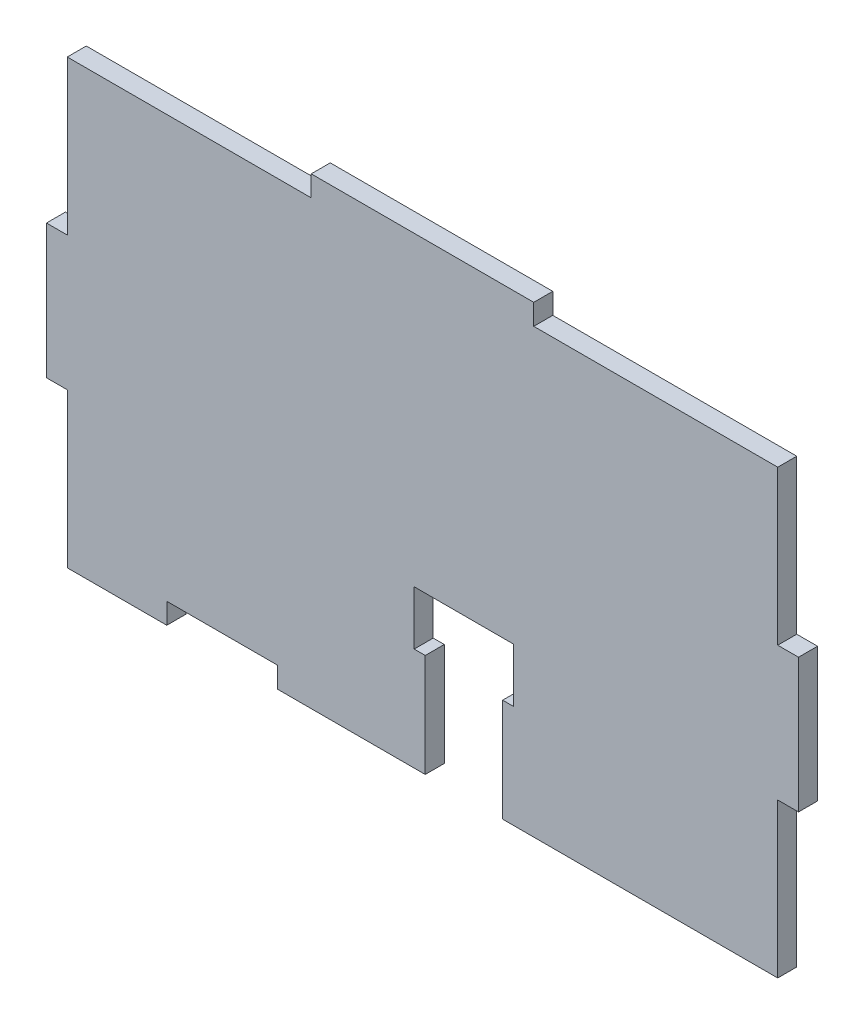
SolidWorks part; units mm, degrees
ref_plane "Front Plane" through (0, 0, 0) normal (0, 0, 1) x (1, 0, 0)
ref_plane "Top Plane" through (0, 0, 0) normal (0, 1, 0) x (1, 0, 0)
ref_plane "Right Plane" through (0, 0, 0) normal (1, 0, 0) x (0, 0, -1)
sketch "Sketch1" plane through (0, 0, 0) normal (0, 0, 1) x (1, 0, 0)
  line L0 (105.85, 0) -> (160.6, 0)
  line L1 (0, 0) -> (22.5, 0)
  line L2 (0, 0) -> (0, 34.85)
  line L3 (0, 100) -> (55.15, 100)
  line L4 (160.6, 0) -> (160.6, 34.85)
  line L6 (78.42, 23.3) -> (78.42, 35.5)
  line L7 (78.42, 35.5) -> (100.92, 35.5)
  line L8 (100.92, 23.3) -> (100.92, 35.5)
  line L9 (100.92, 23.3) -> (98.42, 23.3)
  line L10 (98.42, 23.3) -> (98.42, 0)
  line L11 (98.42, 0) -> (105.85, 0)
  line L12 (78.42, 23.3) -> (80.92, 23.3)
  line L13 (80.92, 23.3) -> (80.92, 0)
  line L14 (80.92, 0) -> (65.85, 0)
  line L15 (160.6, 65.15) -> (160.6, 100)
  line L16 (160.6, 34.85) -> (165.3, 34.85)
  line L18 (160.6, 65.15) -> (165.3, 65.15)
  line L19 (165.3, 34.85) -> (165.3, 65.15)
  line L20 (105.45, 100) -> (160.6, 100)
  line L21 (0, 65.15) -> (0, 100)
  line L22 (-4.7, 34.85) -> (0, 34.85)
  line L23 (-4.7, 34.85) -> (-4.7, 65.15)
  line L24 (-4.7, 65.15) -> (0, 65.15)
  line L26 (47.5, 0) -> (65.85, 0)
  line L29 (55.15, 100) -> (55.15, 104.7)
  line L30 (55.15, 104.7) -> (105.45, 104.7)
  line L31 (105.45, 100) -> (105.45, 104.7)
  line L32 (22.5, 0) -> (22.5, 4.7)
  line L33 (22.5, 4.7) -> (47.5, 4.7)
  line L34 (47.5, 0) -> (47.5, 4.7)
  point P9 (80.3, 104.7)
  point P18 (79.67, 23.3)
  point P32 (165.3, 50)
  point P33 (-4.7, 50)
  point P34 (35, 4.7)
  dimension "D1" = 100
  dimension "D2" = 160.6
  dimension "D3" = 62.18
  dimension "D4" = 22.5
  dimension "D5" = 35.5
  dimension "D6" = 80.3
  dimension "D7" = 50
  dimension "D8" = 12.2
  dimension "D9" = 2.5
  dimension "D10" = 2.5
  dimension "D11" = 50
  dimension "D12" = 30.3
  dimension "D13" = 30.3
  dimension "D14" = 50.3
  dimension "D15" = 4.7
  dimension "D16" = 4.7
  dimension "D17" = 4.7
  dimension "D18" = 25
  dimension "D19" = 4.7
  dimension "D20" = 35
extrude "Boss-Extrude1" add sketch "Sketch1" along normal blind 4.3
